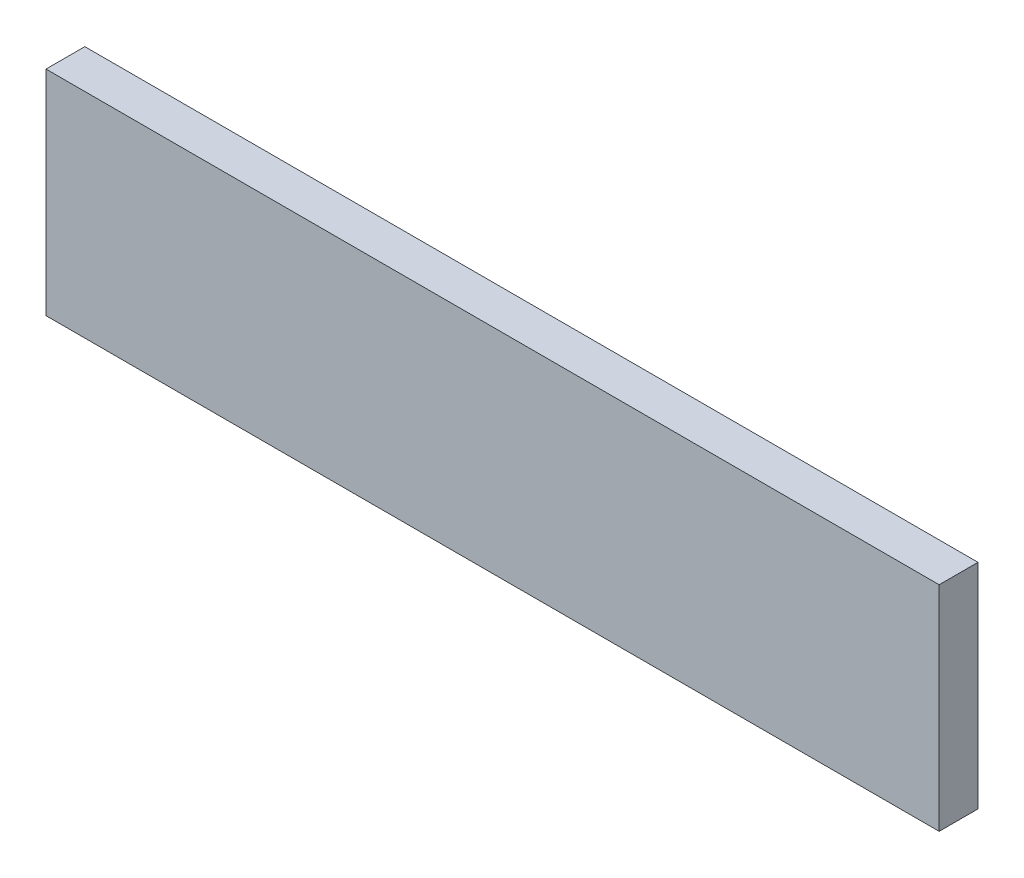
SolidWorks part; units mm, degrees
ref_plane "Front Plane" through (0, 0, 0) normal (0, 0, 1) x (1, 0, 0)
ref_plane "Top Plane" through (0, 0, 0) normal (0, 1, 0) x (1, 0, 0)
ref_plane "Right Plane" through (0, 0, 0) normal (1, 0, 0) x (0, 0, -1)
sketch "Sketch1" plane through (0, 0, 0) normal (0, 0, 1) x (1, 0, 0)
  line L1 (-73.025, -17.4625) -> (73.025, -17.4625)
  line L2 (-73.025, -17.4625) -> (-73.025, 17.4625)
  line L3 (-73.025, 17.4625) -> (73.025, 17.4625)
  line L4 (73.025, -17.4625) -> (73.025, 17.4625)
  line L5 (-73.025, -17.4625) -> (73.025, 17.4625) construction
  line L6 (-73.025, 17.4625) -> (73.025, -17.4625) construction
  point P0 (0, 0)
  dimension "D1" = 146.05
  dimension "D2" = 34.925
extrude "Boss-Extrude1" add sketch "Sketch1" along normal mid plane 6.35
